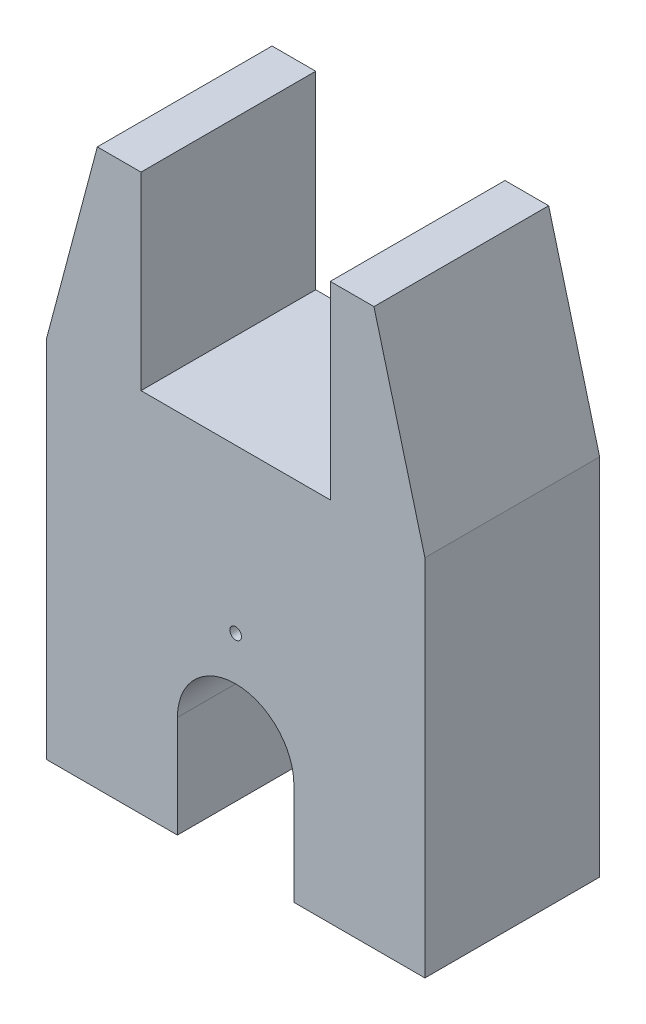
SolidWorks part; units mm, degrees
material "Malleable Cast Iron"
ref_plane "Front Plane" through (0, 0, 0) normal (0, 0, 1) x (1, 0, 0)
ref_plane "Top Plane" through (0, 0, 0) normal (0, 1, 0) x (1, 0, 0)
ref_plane "Right Plane" through (0, 0, 0) normal (1, 0, 0) x (0, 0, -1)
ref_plane "Plane1" through (0, 0, 1524) normal (0, 0, 1) x (1, 0, 0)
sketch "Sketch1" plane through (0, 0, 1524) normal (0, 0, 1) x (1, 0, 0)
  line L0 (-1651, 2286) -> (-1651, -889)
  line L1 (-1651, -889) -> (1651, -889)
  line L2 (1651, -889) -> (1651, 2286)
  line L3 (1651, 2286) -> (1206.5, 3960.876)
  line L4 (1206.5, 3960.876) -> (-1206.5, 3960.876)
  line L5 (-1206.5, 3960.876) -> (-1651, 2286)
extrude "Boss-Extrude1" add sketch "Sketch1" against normal blind 1524
sketch "Sketch2" plane through (0, 0, 0) normal (0, 0, -1) x (-1, 0, 0)
  line L0 (-508, -889) -> (508, -889)
  line L1 (508, -889) -> (508, 0)
  line L2 (-508, 0) -> (-508, -889)
  arc A0 (508, 0) -> (-508, 0) centre (0, 0) ccw
extrude "Cut-Extrude1" cut sketch "Sketch2" against normal through all
sketch "Sketch3" plane through (0, 0, 0) normal (0, 0, -1) x (-1, 0, 0)
  line L0 (825.5, 3960.876) -> (-825.5, 3960.876)
  line L1 (-825.5, 3960.876) -> (-825.5, 2309.876)
  line L2 (-825.5, 2309.876) -> (825.5, 2309.876)
  line L3 (825.5, 2309.876) -> (825.5, 3960.876)
extrude "Cut-Extrude2" cut sketch "Sketch3" against normal through all
hole_wizard "Hole1" positions "Sketch5" profile "Sketch4" legacy
sketch "Sketch5" plane through (0, 0, 1524) normal (0, 0, 1) x (1, 0, 0)
  point P0 (0, 889)
sketch "Sketch4" plane through (0, 889, 1524) normal (1, 0, 0) x (0, -1, 0)
  line L0 (0, 0) -> (0, 792.5237)
  line L1 (0, 792.5237) -> (50.8, 762)
  line L2 (50.8, 762) -> (50.8, 0)
  line L4 (50.8, 0) -> (0, 0)
  line L6 (0, 792.5237) -> (-50.8, 762) construction
  line L7 (0, -4.2442) -> (0, 117.3081) construction
  dimension "Diameter" = 101.6
  dimension "Depth" = 762
  dimension "Drill Angle" = 118
